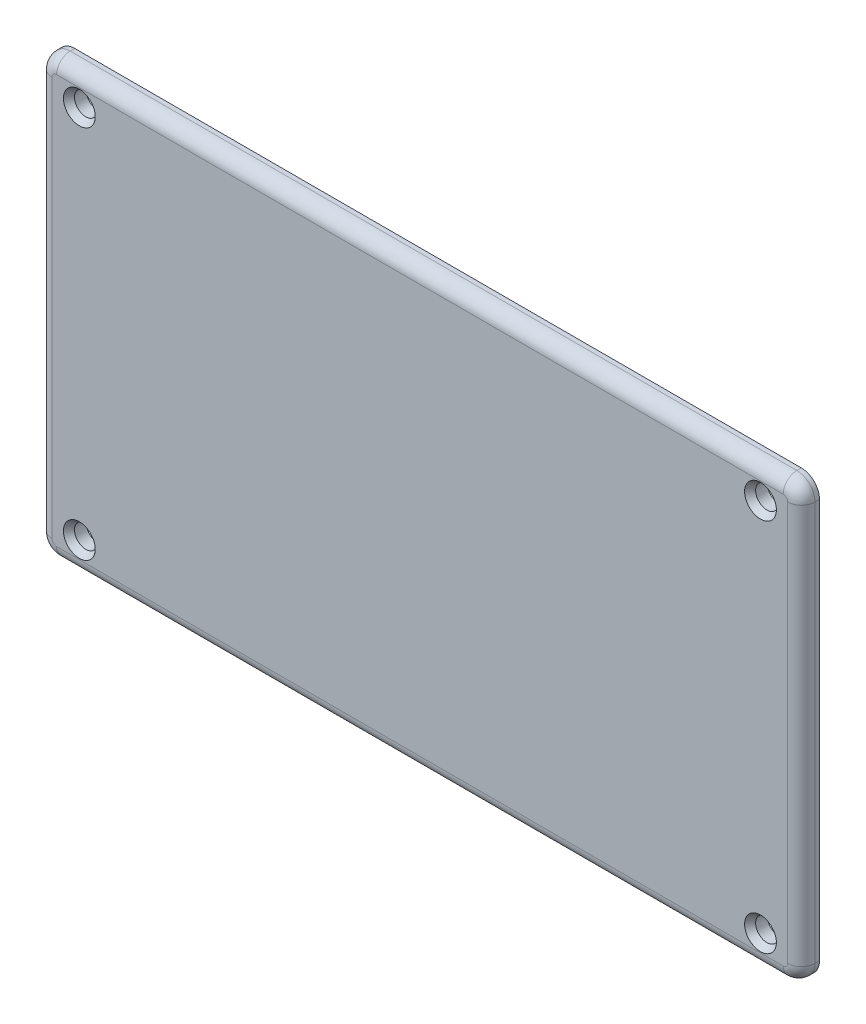
SolidWorks part; units mm, degrees
ref_plane "前视基准面" through (0, 0, 0) normal (0, 0, 1) x (1, 0, 0)
ref_plane "上视基准面" through (0, 0, 0) normal (0, 1, 0) x (1, 0, 0)
ref_plane "右视基准面" through (0, 0, 0) normal (1, 0, 0) x (0, 0, -1)
other "Configuration Table"
sketch "草图2" plane through (0, 0, -23.3854) normal (0, 0, 1) x (1, 0, 0)
  line L12 (-42, 22) -> (-42, -22)
  line L13 (-40, -24) -> (40, -24)
  line L14 (42, -22) -> (42, 22)
  line L15 (40, 24) -> (-40, 24)
  arc A12 (-40, 24) -> (-42, 22) centre (-40, 22) ccw
  arc A13 (-42, -22) -> (-40, -24) centre (-40, -22) ccw
  arc A14 (40, -24) -> (42, -22) centre (40, -22) ccw
  arc A15 (42, 22) -> (40, 24) centre (40, 22) ccw
  circle A16 centre (37.5, -20.625) radius 1.25
  circle A17 centre (-37.5, -20.625) radius 1.25
  circle A18 centre (37.5, 20.625) radius 1.25
  circle A19 centre (-37.5, 20.625) radius 1.25
extrude "凸台-拉伸1" add sketch "草图2" along normal blind 2
fillet "圆角1" radius 1.5 8 edges at (-41.4142, 23.4142, -21.3854) (0, 24, -21.3854) (41.4142, 23.4142, -21.3854) (42, 0, -21.3854) (41.4142, -23.4142, -21.3854) (-42, 0, -21.3854) (-41.4142, -23.4142, -21.3854) (0, -24, -21.3854)
chamfer "倒角1" distance 0.5 angle 55 4 edges at (38.75, 20.625, -21.3854) (38.75, -20.625, -21.3854) (-36.25, -20.625, -21.3854) (-36.25, 20.625, -21.3854)
